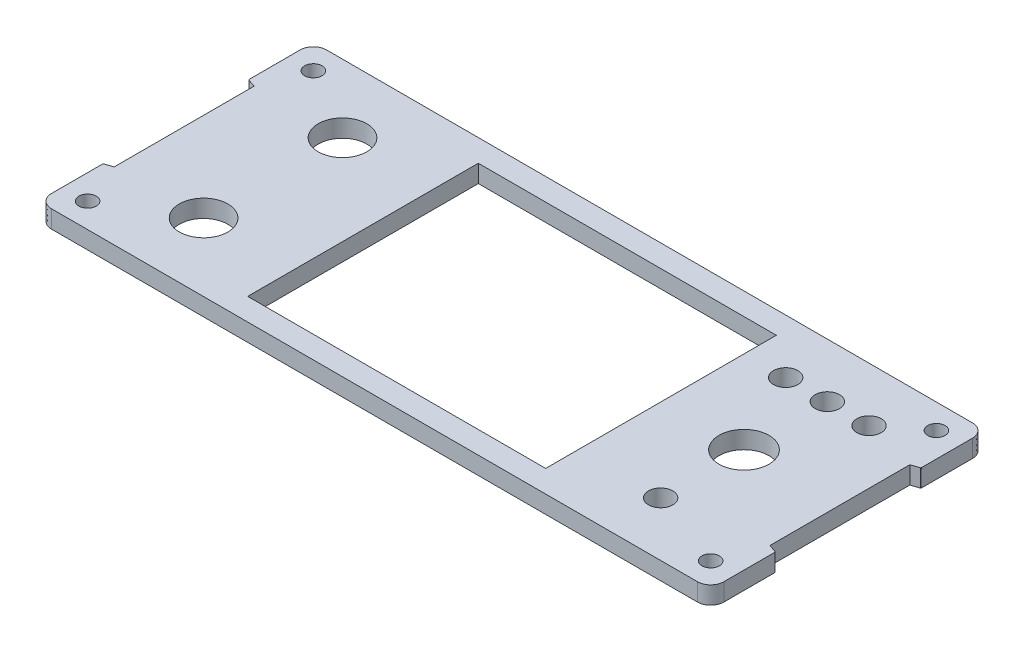
SolidWorks part; units mm, degrees
ref_plane "前视基准面" through (0, 0, 0) normal (0, 0, 1) x (1, 0, 0)
ref_plane "上视基准面" through (0, 0, 0) normal (0, 1, 0) x (1, 0, 0)
ref_plane "右视基准面" through (0, 0, 0) normal (1, 0, 0) x (0, 0, -1)
sketch "草图1" plane through (0, 0, 0) normal (0, 1, 0) x (1, 0, 0)
  line L0 (-34.4, -0.1) -> (-34.4, -39.7) construction
  line L1 (-21.45, -36.5) -> (21.45, -36.5)
  line L2 (-21.45, -36.5) -> (-21.45, -3.3)
  line L3 (-21.45, -3.3) -> (21.45, -3.3)
  line L4 (21.45, -36.5) -> (21.45, -3.3)
  line L5 (-21.45, -36.5) -> (21.45, -3.3) construction
  line L6 (-21.45, -3.3) -> (21.45, -36.5) construction
  line L7 (-27.35, -37.75) -> (23.85, -37.75) construction
  line L8 (-27.35, -37.75) -> (-27.35, -2.05) construction
  line L9 (-27.35, -2.05) -> (23.85, -2.05) construction
  line L10 (23.85, -37.75) -> (23.85, -2.05) construction
  line L11 (-27.35, -37.75) -> (23.85, -2.05) construction
  line L12 (-27.35, -2.05) -> (23.85, -37.75) construction
  line L13 (-47.2, -19.9) -> (47.2, -19.9) construction
  line L14 (33.4, -0.1) -> (33.4, -39.7) construction
  line L15 (0, 0) -> (0, -39.7) construction
  line L16 (27.4, -7.9) -> (39.4, -7.9) construction
  line L21 (24.4, -10.9) -> (30.4, -10.9) construction
  line L22 (24.4, -10.9) -> (24.4, -4.9) construction
  line L24 (48.4, -37.8) -> (48.4, -30.4442)
  line L25 (48.3316, -30.3493) -> (47.2, -29.9721)
  line L26 (47.2, -29.9721) -> (47.2, -9.8279)
  line L27 (47.2, -9.8279) -> (48.3316, -9.4507)
  line L28 (48.4, -9.3558) -> (48.4, -2)
  line L29 (46.5, -0.1) -> (-46.5, -0.1)
  line L30 (-48.4, -2) -> (-48.4, -9.3558)
  line L31 (-48.3316, -9.4507) -> (-47.2, -9.8279)
  line L32 (-47.2, -9.8279) -> (-47.2, -29.9721)
  line L33 (-47.2, -29.9721) -> (-48.3316, -30.3493)
  line L34 (-48.4, -30.4442) -> (-48.4, -37.8)
  line L35 (-46.5, -39.7) -> (46.5, -39.7)
  line L36 (24.4, -4.9) -> (30.4, -4.9) construction
  line L37 (30.4, -10.9) -> (30.4, -4.9) construction
  line L38 (24.4, -10.9) -> (30.4, -4.9) construction
  line L39 (24.4, -4.9) -> (30.4, -10.9) construction
  line L40 (30.4, -4.9) -> (36.4, -10.9) construction
  line L41 (30.4, -10.9) -> (30.4, -4.9) construction
  line L42 (30.4, -4.9) -> (36.4, -4.9) construction
  line L43 (30.4, -10.9) -> (36.4, -10.9) construction
  line L44 (36.4, -10.9) -> (36.4, -4.9) construction
  line L45 (30.4, -10.9) -> (36.4, -4.9) construction
  line L46 (36.4, -4.9) -> (42.4, -10.9) construction
  line L47 (36.4, -10.9) -> (36.4, -4.9) construction
  line L48 (36.4, -4.9) -> (42.4, -4.9) construction
  line L49 (36.4, -10.9) -> (42.4, -10.9) construction
  line L50 (42.4, -10.9) -> (42.4, -4.9) construction
  line L51 (36.4, -10.9) -> (42.4, -4.9) construction
  line L52 (30.4, -34.9) -> (30.4, -28.9) construction
  line L53 (30.4, -28.9) -> (36.4, -34.9) construction
  line L54 (36.4, -34.9) -> (36.4, -28.9) construction
  line L55 (30.4, -34.9) -> (36.4, -28.9) construction
  line L56 (30.4, -28.9) -> (36.4, -28.9) construction
  line L57 (30.4, -34.9) -> (36.4, -34.9) construction
  line L59 (27.4, -25.9) -> (39.4, -25.9) construction
  line L60 (27.4, -25.9) -> (27.4, -13.9) construction
  line L61 (27.4, -13.9) -> (39.4, -13.9) construction
  line L62 (39.4, -25.9) -> (39.4, -13.9) construction
  line L63 (27.4, -25.9) -> (39.4, -13.9) construction
  line L64 (27.4, -13.9) -> (39.4, -25.9) construction
  circle A0 centre (-34.4, -9.9) radius 3.5
  circle A1 centre (-34.4, -29.9) radius 3.5
  circle A2 centre (-34.4, -9.9) radius 6 construction
  circle A3 centre (-34.4, -29.9) radius 6 construction
  circle A4 centre (33.4, -19.9) radius 3.6
  circle A5 centre (-44.85, -36.15) radius 1.25
  circle A6 centre (33.4, -19.9) radius 8 construction
  circle A7 centre (44.85, -36.15) radius 1.25
  circle A9 centre (27.4, -7.9) radius 1.75
  circle A10 centre (-44.85, -3.65) radius 1.25
  circle A11 centre (44.85, -3.65) radius 1.25
  circle A12 centre (39.4, -7.9) radius 1.75
  circle A13 centre (33.4, -31.9) radius 1.75
  circle A15 centre (33.4, -7.9) radius 1.75
  spline S16 degree 2 poles (46.5, -39.7) (46.8776, -39.7) (47.2271, -39.5554) (47.5758, -39.4111) (47.8435, -39.1435) (48.1104, -38.8767) (48.2554, -38.5271) (48.4, -38.1782) (48.4, -37.8) knots 0 0 0 0.25 0.25 0.5 0.5 0.75 0.75 1 1 1
  spline S17 degree 2 poles (48.4, -30.4442) (48.4, -30.4122) (48.3811, -30.3857) (48.3625, -30.3596) (48.3316, -30.3493) knots 0 0 0 0.5 0.5 1 1 1
  spline S18 degree 2 poles (48.3316, -9.4507) (48.3619, -9.4406) (48.3811, -9.4143) (48.4, -9.3884) (48.4, -9.3558) knots 0 0 0 0.5 0.5 1 1 1
  spline S19 degree 2 poles (48.4, -2) (48.4, -1.6224) (48.2554, -1.2729) (48.1111, -0.9242) (47.8435, -0.6565) (47.5767, -0.3896) (47.2271, -0.2446) (46.8782, -0.1) (46.5, -0.1) knots 0 0 0 0.25 0.25 0.5 0.5 0.75 0.75 1 1 1
  spline S20 degree 2 poles (-46.5, -0.1) (-46.8776, -0.1) (-47.2271, -0.2446) (-47.5758, -0.3889) (-47.8435, -0.6565) (-48.1104, -0.9233) (-48.2554, -1.2729) (-48.4, -1.6218) (-48.4, -2) knots 0 0 0 0.25 0.25 0.5 0.5 0.75 0.75 1 1 1
  spline S21 degree 2 poles (-48.4, -9.3558) (-48.4, -9.3878) (-48.3811, -9.4143) (-48.3625, -9.4404) (-48.3316, -9.4507) knots 0 0 0 0.5 0.5 1 1 1
  spline S22 degree 2 poles (-48.3316, -30.3493) (-48.3619, -30.3594) (-48.3811, -30.3857) (-48.4, -30.4116) (-48.4, -30.4442) knots 0 0 0 0.5 0.5 1 1 1
  spline S23 degree 2 poles (-48.4, -37.8) (-48.4, -38.1776) (-48.2554, -38.5271) (-48.1111, -38.8758) (-47.8435, -39.1435) (-47.5767, -39.4104) (-47.2271, -39.5554) (-46.8782, -39.7) (-46.5, -39.7) knots 0 0 0 0.25 0.25 0.5 0.5 0.75 0.75 1 1 1
  point P4 (0, -19.9)
  point P16 (-1.75, -19.9)
  point P49 (-34.4, -19.9)
  dimension "D8" = 15
  dimension "D9" = 7
  dimension "D10" = 12
  dimension "D11" = 7.2
  dimension "D12" = 16
  dimension "D13" = 6
  dimension "D14" = 6
  dimension "D15" = 3.5
  dimension "D16" = 6
  dimension "D1" = 5.9
  dimension "D2" = 42.9
  dimension "D3" = 33.2
  dimension "D4" = 51.2
  dimension "D5" = 35.7
  dimension "D6" = 14
  dimension "D7" = 10
  dimension "D17" = 12
  dimension "D18" = 12
  dimension "D19" = 12
extrude "凸台-拉伸1" add sketch "草图1" along normal blind 2.54
sketch "草图3" plane through (0, 2.54, 0) normal (0, 1, 0) x (1, 0, 0)
  line L17 (42.5, -2) -> (42.5, -3.6978)
  line L18 (43, -35.4313) -> (43, -4.3687)
  line L19 (42.5, -36.1022) -> (42.5, -37.8)
  line L20 (-42.5, -37.8) -> (42.5, -37.8)
  line L21 (-42.5, -36.1022) -> (-42.5, -37.8)
  line L22 (-43, -4.3687) -> (-43, -35.4313)
  line L23 (-42.5, -2) -> (-42.5, -3.6978)
  line L24 (42.5, -2) -> (-42.5, -2)
  line L25 (30.4, -4.9) -> (36.4, -4.9)
  line L26 (24.4, -10.9) -> (30.4, -10.9)
  line L27 (24.4, -10.9) -> (24.4, -4.9)
  line L28 (24.4, -4.9) -> (30.4, -4.9)
  line L29 (-21.45, -36.5) -> (21.45, -36.5)
  line L30 (21.45, -36.5) -> (21.45, -3.3)
  line L31 (21.45, -3.3) -> (-21.45, -3.3)
  line L32 (-21.45, -3.3) -> (-21.45, -36.5)
  line L34 (24.4, -10.9) -> (30.4, -4.9) construction
  line L35 (24.4, -4.9) -> (30.4, -10.9) construction
  line L36 (30.4, -4.9) -> (36.4, -10.9) construction
  line L37 (36.4, -10.9) -> (42.4, -10.9)
  line L38 (30.4, -10.9) -> (36.4, -4.9) construction
  line L39 (30.4, -10.9) -> (36.4, -10.9)
  line L40 (36.4, -4.9) -> (42.4, -10.9) construction
  line L41 (36.4, -10.9) -> (42.4, -4.9) construction
  line L42 (36.4, -4.9) -> (42.4, -4.9)
  line L43 (42.4, -10.9) -> (42.4, -4.9)
  line L44 (30.4, -34.9) -> (30.4, -28.9)
  line L45 (30.4, -28.9) -> (36.4, -28.9)
  line L46 (30.4, -34.9) -> (36.4, -34.9)
  line L47 (30.4, -34.9) -> (36.4, -28.9) construction
  line L48 (30.4, -28.9) -> (36.4, -34.9) construction
  line L49 (36.4, -34.9) -> (36.4, -28.9)
  line L51 (27.4, -25.9) -> (39.4, -25.9)
  line L52 (27.4, -25.9) -> (27.4, -13.9)
  line L53 (27.4, -13.9) -> (39.4, -13.9)
  line L54 (39.4, -25.9) -> (39.4, -13.9)
  line L55 (27.4, -25.9) -> (39.4, -13.9) construction
  line L56 (27.4, -13.9) -> (39.4, -25.9) construction
  circle A0 centre (33.4, -31.9) radius 1.75 construction
  arc A1 (-48.5, -37.8) -> (-46.5, -39.8) centre (-46.5, -37.8) ccw
  circle A2 centre (-34.4, -9.9) radius 3.5
  circle A4 centre (33.4, -19.9) radius 3.6 construction
  arc A5 (-45.2011, -37.3497) -> (-43.6503, -35.7989) centre (-44.85, -36.15) ccw
  circle A6 centre (-34.4, -29.9) radius 3.5
  circle A8 centre (33.4, -31.9) radius 1.75
  arc A10 (42.5, -3.6978) -> (43, -4.3687) centre (43.2, -3.6978) ccw
  circle A12 centre (33.4, -19.9) radius 3.6
  arc A23 (43, -35.4313) -> (42.5, -36.1022) centre (43.2, -36.1022) ccw
  arc A24 (-42.5, -36.1022) -> (-43, -35.4313) centre (-43.2, -36.1022) ccw
  arc A25 (-43, -4.3687) -> (-42.5, -3.6978) centre (-43.2, -3.6978) ccw
  point P31 (27.4, -7.9)
  point P56 (33.4, -31.9)
  dimension "D1" = 6
  dimension "D2" = 6
  dimension "D3" = 6
  dimension "D4" = 12
  dimension "D5" = 12
